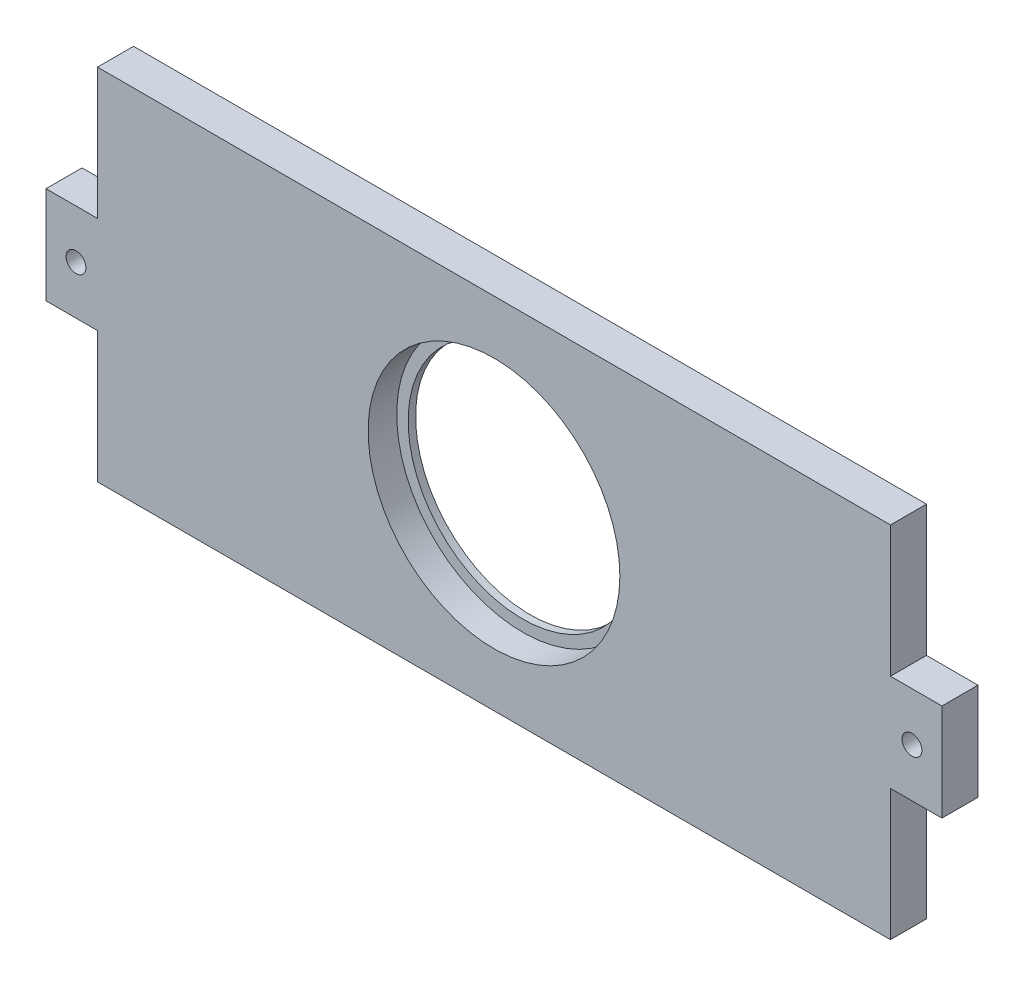
SolidWorks part; units mm, degrees
ref_plane "Front Plane" through (0, 0, 0) normal (0, 0, 1) x (1, 0, 0)
ref_plane "Top Plane" through (0, 0, 0) normal (0, 1, 0) x (1, 0, 0)
ref_plane "Right Plane" through (0, 0, 0) normal (1, 0, 0) x (0, 0, -1)
sketch "Sketch1" plane through (0, 0, 0) normal (0, 0, 1) x (1, 0, 0)
  line L0 (-44, 19.9319) -> (-44, 5.39)
  line L1 (44, -19.9319) -> (-44, -19.9319)
  line L2 (44, -19.9319) -> (44, 19.9319) construction
  line L3 (44, 19.9319) -> (-44, 19.9319)
  line L4 (-44, -19.9319) -> (-44, 19.9319) construction
  line L5 (44, -19.9319) -> (-44, 19.9319) construction
  line L6 (44, 19.9319) -> (-44, -19.9319) construction
  line L7 (-44, 5.39) -> (-49.715, 5.39)
  line L8 (-49.715, 5.39) -> (-49.715, -5.39)
  line L9 (-49.715, 0) -> (-44, 0) construction
  line L10 (0, 19.9319) -> (0, -19.9319) construction
  line L11 (-44, -5.39) -> (-49.715, -5.39)
  line L12 (-44, -19.9319) -> (-44, -5.39)
  line L13 (44, -19.9319) -> (44, -5.39)
  line L14 (44, -5.39) -> (49.715, -5.39)
  line L15 (49.715, 5.39) -> (49.715, -5.39)
  line L16 (44, 5.39) -> (49.715, 5.39)
  line L17 (44, 19.9319) -> (44, 5.39)
  circle A0 centre (0, 0) radius 12.7
  circle A1 centre (-46.3876, 0) radius 1.1
  circle A2 centre (46.3876, 0) radius 1.1
  point P0 (0, 0)
  dimension "D1" = 25.4
  dimension "D7" = 2.2
  dimension "D2" = 39.8638
  dimension "D3" = 88
  dimension "D4" = 5.715
  dimension "D5" = 10.78
  dimension "D6" = 2.3876
extrude "Boss-Extrude1" add sketch "Sketch1" along normal blind 4
sketch "Sketch2" plane through (0, 0, 4) normal (0, 0, 1) x (1, 0, 0)
  circle A0 centre (0, 0) radius 13.97
  dimension "D1" = 27.94
extrude "Cut-Extrude1" cut sketch "Sketch2" against normal blind 3.175
